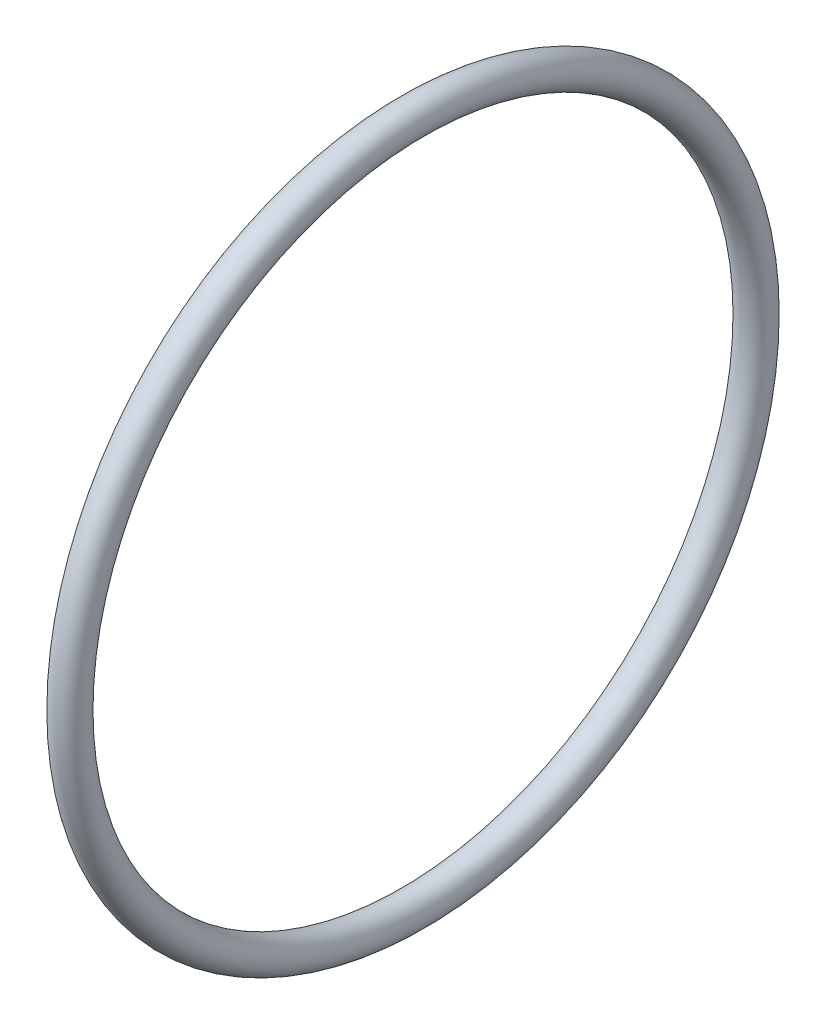
SolidWorks part; units mm, degrees
ref_plane "Front Plane" through (0, 0, 0) normal (0, 0, 1) x (1, 0, 0)
ref_plane "Top Plane" through (0, 0, 0) normal (0, 1, 0) x (1, 0, 0)
ref_plane "Right Plane" through (0, 0, 0) normal (1, 0, 0) x (0, 0, -1)
sketch "Sketch1" plane through (0, 0, 0) normal (0, 0, 1) x (1, 0, 0)
  line L0 (0, -0.75) -> (0, -15.75) construction
  line L1 (-2.6651, -15.75) -> (3.5672, -15.75) construction
  circle A0 centre (0, 0) radius 0.75
  dimension "D1" = 1.5
  dimension "D2" = 15
revolve "Revolve1" add sketch "Sketch1" angle 360 about L1
sketch "Sketch2" plane through (0, 0, 0) normal (1, 0, 0) x (0, 0, -1)
  circle A0 centre (0, -15.75) radius 15 construction
  circle A1 centre (0, -15.75) radius 15
